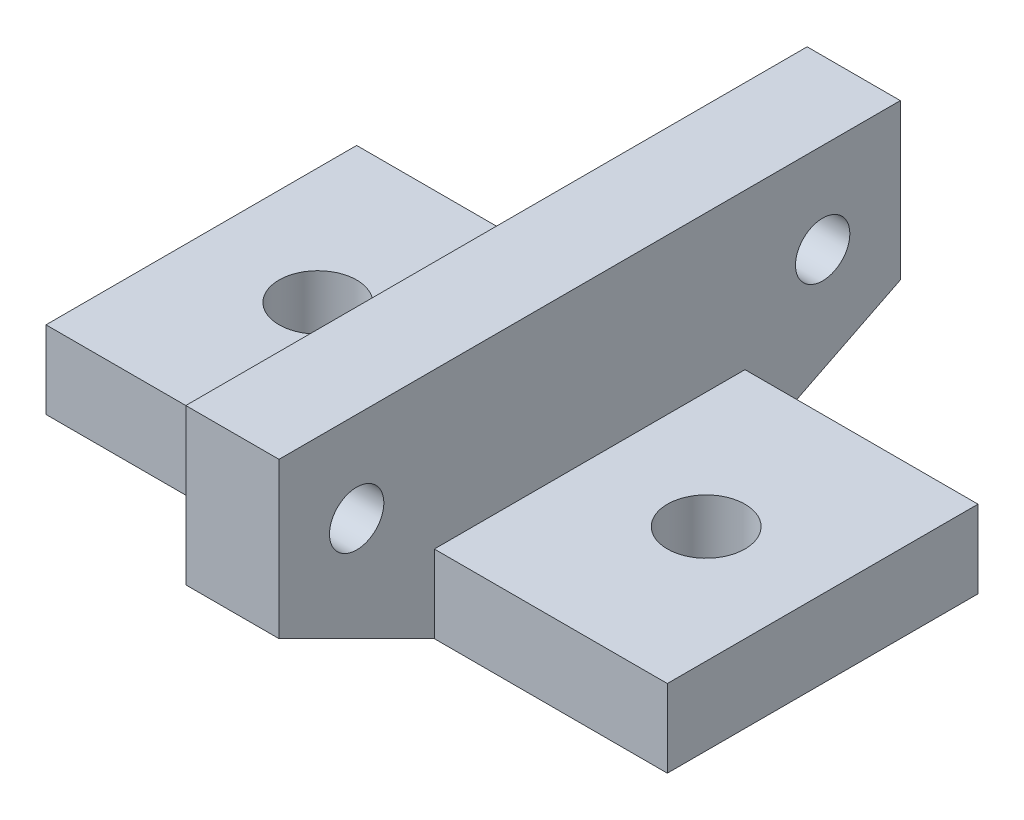
SolidWorks part; units mm, degrees
ref_plane "前视基准面" through (0, 0, 0) normal (0, 0, 1) x (1, 0, 0)
ref_plane "上视基准面" through (0, 0, 0) normal (0, 1, 0) x (1, 0, 0)
ref_plane "右视基准面" through (0, 0, 0) normal (1, 0, 0) x (0, 0, -1)
sketch "草图1" plane through (0, 0, 0) normal (0, 1, 0) x (1, 0, 0)
  line L0 (0, 0) -> (0, 10) construction
  line L1 (-20, 10) -> (20, 10)
  line L2 (-20, 10) -> (-20, -10)
  line L3 (-20, -10) -> (20, -10)
  line L4 (20, 10) -> (20, -10)
  line L5 (-20, 10) -> (20, -10) construction
  line L6 (-20, -10) -> (20, 10) construction
  circle A0 centre (-12.5, 0) radius 2.5
  circle A1 centre (12.5, 0) radius 2.5
  point P0 (0, 0)
  dimension "D3" = 5
  dimension "D1" = 20
  dimension "D2" = 40
  dimension "D4" = 25
extrude "凸台-拉伸1" add sketch "草图1" along normal blind 5
sketch "草图2" plane through (0, 5, 0) normal (0, 1, 0) x (1, 0, 0)
  line L0 (-20, 10) -> (-20, -10) construction
  line L1 (-1, 20) -> (5, 20)
  line L2 (-1, 20) -> (-1, -20)
  line L3 (-1, -20) -> (5, -20)
  line L4 (5, 20) -> (5, -20)
  line L5 (-1, 20) -> (5, -20) construction
  line L6 (-1, -20) -> (5, 20) construction
  line L7 (20, 10) -> (-20, 10) construction
  line L8 (0, 10) -> (0, -10) construction
  line L9 (-20, -10) -> (20, -10) construction
  point P0 (2, 0)
  point P8 (-20, 0)
  point P16 (0, 0)
  dimension "D1" = 6
  dimension "D2" = 40
  dimension "D3" = 1
extrude "凸台-拉伸2" add sketch "草图2" along normal blind 10
sketch "草图3" plane through (5, 0, 0) normal (1, 0, 0) x (0, 0, -1)
  line L0 (0, 15) -> (0, 5) construction
  line L1 (-20, 15) -> (20, 15) construction
  line L2 (-10, 5) -> (10, 5) construction
  line L3 (-20, 5) -> (-10, 5) construction
  circle A0 centre (-15, 9.2) radius 1.75
  circle A1 centre (15, 9.2) radius 1.75
  dimension "D1" = 3.5
  dimension "D2" = 30
  dimension "D3" = 4.2
extrude "切除-拉伸1" cut sketch "草图3" against normal blind 10
sketch "草图4" plane through (5, 0, 0) normal (1, 0, 0) x (0, 0, -1)
  line L0 (-20, 5) -> (-10, 0)
  line L1 (-10, 0) -> (-10, 5)
  line L2 (-10, 5) -> (-20, 5)
  line L3 (10, 5) -> (10, 0)
  line L4 (10, 0) -> (20, 5)
  line L5 (20, 5) -> (10, 5)
extrude "凸台-拉伸3" add sketch "草图4" against normal up to surface (6 mm away) up to face at (-1, 9.2, 13.25)
